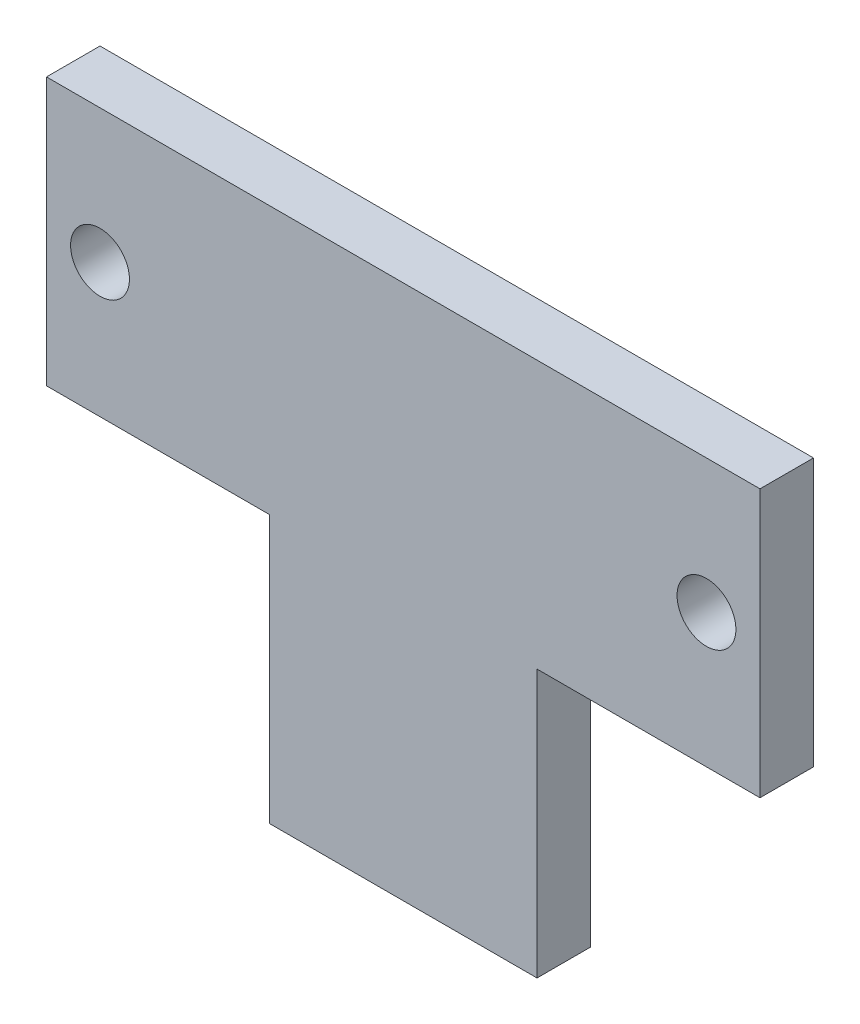
SolidWorks part; units mm, degrees
ref_plane "Plan de face" through (0, 0, 0) normal (0, 0, 1) x (1, 0, 0)
ref_plane "Plan de dessus" through (0, 0, 0) normal (0, 1, 0) x (1, 0, 0)
ref_plane "Plan de droite" through (0, 0, 0) normal (1, 0, 0) x (0, 0, -1)
sketch "Esquisse1" plane through (0, 0, 0) normal (0, 0, 1) x (1, 0, 0)
  line L0 (-7.5, -7.5) -> (-7.5, -22.5)
  line L1 (-20, -7.5) -> (-7.5, -7.5)
  line L2 (-20, -7.5) -> (-20, 7.5)
  line L3 (-20, 7.5) -> (20, 7.5)
  line L4 (20, -7.5) -> (20, 7.5)
  line L5 (-20, -7.5) -> (20, 7.5) construction
  line L6 (-20, 7.5) -> (20, -7.5) construction
  line L7 (-7.5, -22.5) -> (7.5, -22.5)
  line L8 (7.5, -22.5) -> (7.5, -7.5)
  line L9 (7.5, -7.5) -> (20, -7.5)
  circle A0 centre (-17, 0) radius 1.65
  circle A1 centre (17, 0) radius 1.65
  point P0 (0, 0)
  dimension "D3" = 3.3
  dimension "D4" = 3.3
  dimension "D1" = 15
  dimension "D2" = 40
  dimension "D5" = 34
  dimension "D6" = 3
  dimension "D7" = 3
  dimension "D8" = 7.5
  dimension "D9" = 15
  dimension "D10" = 15
  dimension "D11" = 12.5
extrude "Boss.-Extru.1" add sketch "Esquisse1" against normal blind 3
